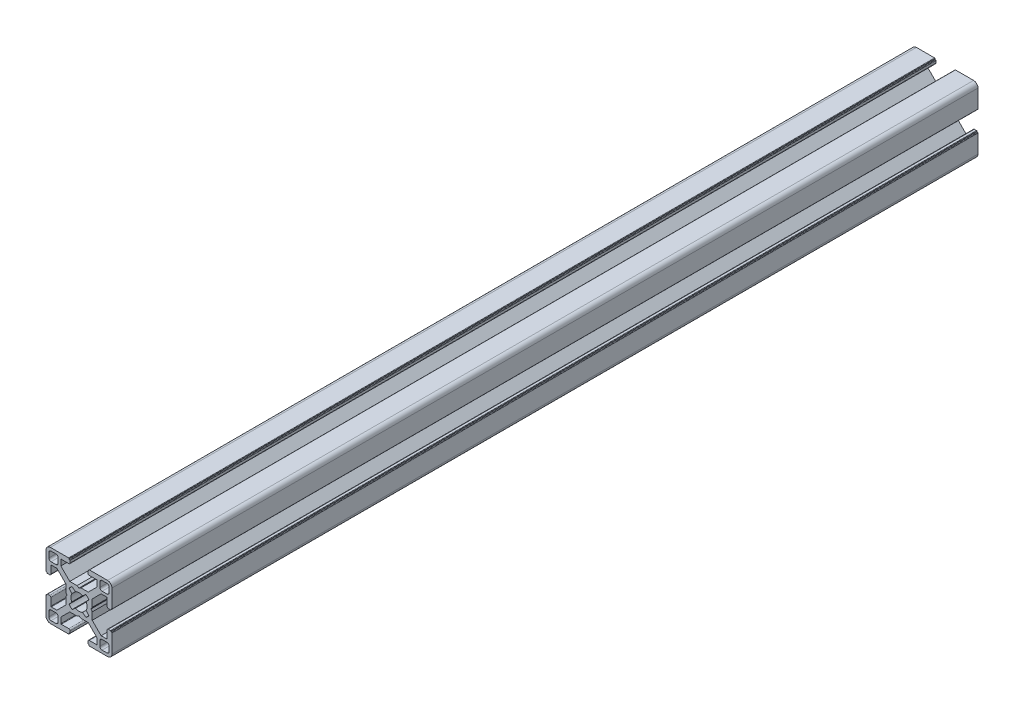
SolidWorks part; units mm, degrees
material "6061 Alloy"
ref_plane "Front" through (0, 0, 0) normal (0, 0, 1) x (1, 0, 0)
ref_plane "Top" through (0, 0, 0) normal (0, 1, 0) x (1, 0, 0)
ref_plane "Right" through (0, 0, 0) normal (1, 0, 0) x (0, 0, -1)
sketch "Sketch1" plane through (0, 0, 0) normal (0, 0, 1) x (1, 0, 0)
  line L0 (13.7, 12.7) -> (13.7, 10.5)
  line L1 (10.5, 9.5) -> (12.7, 9.5)
  line L2 (9.5, 12.7) -> (9.5, 10.5)
  line L3 (10.5, 13.7) -> (12.7, 13.7)
  line L4 (3.1359, 4.5184) -> (1.6001, 3.2806)
  line L5 (3.2806, 1.6001) -> (4.5053, 3.1547)
  line L6 (6.0045, 0.9) -> (5.4849, 0)
  line L7 (6.0045, 4.2045) -> (6.0045, 0.9)
  line L8 (0, -5.4849) -> (0.9, -6)
  line L9 (0.9, -6) -> (4.2045, -6)
  line L10 (4.2045, -6) -> (8.25, -10.05)
  line L11 (8.25, -10.05) -> (8.25, -12.6)
  line L12 (4.65, -12.8) -> (8.05, -12.8)
  line L13 (4.05, -14.3) -> (4.05, -13.4)
  line L14 (4.25, -14.5) -> (4.35, -14.5)
  line L15 (4.55, -14.8) -> (4.55, -14.7)
  line L16 (4.75, -15) -> (13, -15)
  line L17 (15, -13) -> (15, -4.75)
  line L18 (14.7, -4.55) -> (14.8, -4.55)
  line L19 (14.5, -4.35) -> (14.5, -4.25)
  line L20 (13.4, -4.05) -> (14.3, -4.05)
  line L21 (12.8, -8.05) -> (12.8, -4.65)
  line L22 (12.6, -8.25) -> (10.05, -8.25)
  line L23 (10.05, -8.25) -> (6.0045, -4.2045)
  line L24 (6.0045, -4.2045) -> (6.0045, -0.9)
  line L25 (6.0045, -0.9) -> (5.4849, 0)
  line L26 (10.05, 8.25) -> (6.0045, 4.2045)
  line L27 (12.6, 8.25) -> (10.05, 8.25)
  line L28 (12.8, 8.05) -> (12.8, 4.65)
  line L29 (13.4, 4.05) -> (14.3, 4.05)
  line L30 (14.5, 4.35) -> (14.5, 4.25)
  line L31 (14.7, 4.55) -> (14.8, 4.55)
  line L32 (15, 13) -> (15, 4.75)
  line L33 (4.75, 15) -> (13, 15)
  line L34 (4.55, 14.8) -> (4.55, 14.7)
  line L35 (4.25, 14.5) -> (4.35, 14.5)
  line L36 (4.05, 14.3) -> (4.05, 13.4)
  line L37 (4.65, 12.8) -> (8.05, 12.8)
  line L38 (8.25, 10.05) -> (8.25, 12.6)
  line L39 (4.2045, 6) -> (8.25, 10.05)
  line L40 (0.9, 6) -> (4.2045, 6)
  line L41 (0, 5.4849) -> (0.9, 6)
  line L42 (-13.7, -12.7) -> (-13.7, -10.5)
  line L43 (-10.5, -9.5) -> (-12.7, -9.5)
  line L44 (-9.5, -12.7) -> (-9.5, -10.5)
  line L45 (-10.5, -13.7) -> (-12.7, -13.7)
  line L46 (-3.1359, -4.5184) -> (-1.6001, -3.2806)
  line L47 (-3.2806, -1.6001) -> (-4.5053, -3.1547)
  line L48 (0, 5.4849) -> (-0.9, 6)
  line L49 (-0.9, 6) -> (-4.2045, 6)
  line L50 (-4.2045, 6) -> (-8.25, 10.05)
  line L51 (-8.25, 10.05) -> (-8.25, 12.6)
  line L52 (-4.65, 12.8) -> (-8.05, 12.8)
  line L53 (-4.05, 14.3) -> (-4.05, 13.4)
  line L54 (-4.25, 14.5) -> (-4.35, 14.5)
  line L55 (-4.55, 14.8) -> (-4.55, 14.7)
  line L56 (-4.75, 15) -> (-13, 15)
  line L57 (-15, 13) -> (-15, 4.75)
  line L58 (-14.7, 4.55) -> (-14.8, 4.55)
  line L59 (-14.5, 4.35) -> (-14.5, 4.25)
  line L60 (-13.4, 4.05) -> (-14.3, 4.05)
  line L61 (-12.8, 8.05) -> (-12.8, 4.65)
  line L62 (-12.6, 8.25) -> (-10.05, 8.25)
  line L63 (-10.05, 8.25) -> (-6.0045, 4.2045)
  line L64 (-6.0045, -0.9) -> (-5.4849, 0)
  line L65 (-6.0045, -4.2045) -> (-6.0045, -0.9)
  line L66 (-10.05, -8.25) -> (-6.0045, -4.2045)
  line L67 (-12.6, -8.25) -> (-10.05, -8.25)
  line L68 (-12.8, -8.05) -> (-12.8, -4.65)
  line L69 (-13.4, -4.05) -> (-14.3, -4.05)
  line L70 (-14.5, -4.35) -> (-14.5, -4.25)
  line L71 (-14.7, -4.55) -> (-14.8, -4.55)
  line L72 (-15, -13) -> (-15, -4.75)
  line L73 (-4.75, -15) -> (-13, -15)
  line L74 (-4.55, -14.8) -> (-4.55, -14.7)
  line L75 (-4.25, -14.5) -> (-4.35, -14.5)
  line L76 (-4.05, -14.3) -> (-4.05, -13.4)
  line L77 (3.2806, -1.6001) -> (4.5053, -3.1547)
  line L78 (3.1359, -4.5184) -> (1.6001, -3.2806)
  line L79 (-4.65, -12.8) -> (-8.05, -12.8)
  line L80 (-8.25, -10.05) -> (-8.25, -12.6)
  line L81 (-4.2045, -6) -> (-8.25, -10.05)
  line L82 (-0.9, -6) -> (-4.2045, -6)
  line L83 (0, -5.4849) -> (-0.9, -6)
  line L84 (10.5, -13.7) -> (12.7, -13.7)
  line L85 (9.5, -12.7) -> (9.5, -10.5)
  line L86 (10.5, -9.5) -> (12.7, -9.5)
  line L87 (13.7, -12.7) -> (13.7, -10.5)
  line L88 (-6.0045, 4.2045) -> (-6.0045, 0.9)
  line L89 (-6.0045, 0.9) -> (-5.4849, 0)
  line L90 (-3.2806, 1.6001) -> (-4.5053, 3.1547)
  line L91 (-3.1359, 4.5184) -> (-1.6001, 3.2806)
  line L92 (-10.5, 13.7) -> (-12.7, 13.7)
  line L93 (-9.5, 12.7) -> (-9.5, 10.5)
  line L94 (-10.5, 9.5) -> (-12.7, 9.5)
  line L95 (-13.7, 12.7) -> (-13.7, 10.5)
  line L96 (-23.4857, 0) -> (20.9308, 0) construction
  line L97 (0, 17.9563) -> (0, -17.361) construction
  arc A0 (13.7, 12.7) -> (12.7, 13.7) centre (12.7, 12.7) ccw
  arc A1 (12.7, 9.5) -> (13.7, 10.5) centre (12.7, 10.5) ccw
  arc A2 (9.5, 10.5) -> (10.5, 9.5) centre (10.5, 10.5) ccw
  arc A3 (10.5, 13.7) -> (9.5, 12.7) centre (10.5, 12.7) ccw
  arc A4 (1.6001, 3.2806) -> (-1.6001, 3.2806) centre (0, 0) ccw
  arc A5 (8.25, -12.6) -> (8.05, -12.8) centre (8.05, -12.6) cw
  arc A6 (4.65, -12.8) -> (4.05, -13.4) centre (4.65, -13.4) ccw
  arc A7 (4.05, -14.3) -> (4.25, -14.5) centre (4.25, -14.3) ccw
  arc A8 (4.35, -14.5) -> (4.55, -14.7) centre (4.35, -14.7) cw
  arc A9 (4.55, -14.8) -> (4.75, -15) centre (4.75, -14.8) ccw
  arc A10 (13, -15) -> (15, -13) centre (13, -13) ccw
  arc A11 (15, -4.75) -> (14.8, -4.55) centre (14.8, -4.75) ccw
  arc A12 (14.7, -4.55) -> (14.5, -4.35) centre (14.7, -4.35) cw
  arc A13 (14.5, -4.25) -> (14.3, -4.05) centre (14.3, -4.25) ccw
  arc A14 (13.4, -4.05) -> (12.8, -4.65) centre (13.4, -4.65) ccw
  arc A15 (12.8, -8.05) -> (12.6, -8.25) centre (12.6, -8.05) cw
  arc A16 (4.5053, 3.1547) -> (3.1359, 4.5184) centre (0, 0) ccw
  arc A17 (12.8, 8.05) -> (12.6, 8.25) centre (12.6, 8.05) ccw
  arc A18 (13.4, 4.05) -> (12.8, 4.65) centre (13.4, 4.65) cw
  arc A19 (14.5, 4.25) -> (14.3, 4.05) centre (14.3, 4.25) cw
  arc A20 (14.7, 4.55) -> (14.5, 4.35) centre (14.7, 4.35) ccw
  arc A21 (15, 4.75) -> (14.8, 4.55) centre (14.8, 4.75) cw
  arc A22 (13, 15) -> (15, 13) centre (13, 13) cw
  arc A23 (4.55, 14.8) -> (4.75, 15) centre (4.75, 14.8) cw
  arc A24 (4.35, 14.5) -> (4.55, 14.7) centre (4.35, 14.7) ccw
  arc A25 (4.05, 14.3) -> (4.25, 14.5) centre (4.25, 14.3) cw
  arc A26 (4.65, 12.8) -> (4.05, 13.4) centre (4.65, 13.4) cw
  arc A27 (8.25, 12.6) -> (8.05, 12.8) centre (8.05, 12.6) ccw
  arc A28 (-13.7, -12.7) -> (-12.7, -13.7) centre (-12.7, -12.7) ccw
  arc A29 (-12.7, -9.5) -> (-13.7, -10.5) centre (-12.7, -10.5) ccw
  arc A30 (-9.5, -10.5) -> (-10.5, -9.5) centre (-10.5, -10.5) ccw
  arc A31 (-10.5, -13.7) -> (-9.5, -12.7) centre (-10.5, -12.7) ccw
  arc A32 (-4.5053, -3.1547) -> (-3.1359, -4.5184) centre (0, 0) ccw
  arc A33 (-3.2806, 1.6001) -> (-3.2806, -1.6001) centre (0, 0) ccw
  arc A34 (-8.25, 12.6) -> (-8.05, 12.8) centre (-8.05, 12.6) cw
  arc A35 (-4.65, 12.8) -> (-4.05, 13.4) centre (-4.65, 13.4) ccw
  arc A36 (-4.05, 14.3) -> (-4.25, 14.5) centre (-4.25, 14.3) ccw
  arc A37 (-4.35, 14.5) -> (-4.55, 14.7) centre (-4.35, 14.7) cw
  arc A38 (-4.55, 14.8) -> (-4.75, 15) centre (-4.75, 14.8) ccw
  arc A39 (-13, 15) -> (-15, 13) centre (-13, 13) ccw
  arc A40 (-15, 4.75) -> (-14.8, 4.55) centre (-14.8, 4.75) ccw
  arc A41 (-14.7, 4.55) -> (-14.5, 4.35) centre (-14.7, 4.35) cw
  arc A42 (-14.5, 4.25) -> (-14.3, 4.05) centre (-14.3, 4.25) ccw
  arc A43 (-13.4, 4.05) -> (-12.8, 4.65) centre (-13.4, 4.65) ccw
  arc A44 (-12.8, 8.05) -> (-12.6, 8.25) centre (-12.6, 8.05) cw
  arc A45 (-4.5053, 3.1547) -> (-3.1359, 4.5184) centre (0, 0) cw
  arc A46 (-12.8, -8.05) -> (-12.6, -8.25) centre (-12.6, -8.05) ccw
  arc A47 (-13.4, -4.05) -> (-12.8, -4.65) centre (-13.4, -4.65) cw
  arc A48 (-14.5, -4.25) -> (-14.3, -4.05) centre (-14.3, -4.25) cw
  arc A49 (3.2806, 1.6001) -> (3.2806, -1.6001) centre (0, 0) cw
  arc A50 (4.5053, -3.1547) -> (3.1359, -4.5184) centre (0, 0) cw
  arc A51 (1.6001, -3.2806) -> (-1.6001, -3.2806) centre (0, 0) cw
  arc A52 (-14.7, -4.55) -> (-14.5, -4.35) centre (-14.7, -4.35) ccw
  arc A53 (-15, -4.75) -> (-14.8, -4.55) centre (-14.8, -4.75) cw
  arc A54 (-13, -15) -> (-15, -13) centre (-13, -13) cw
  arc A55 (-4.55, -14.8) -> (-4.75, -15) centre (-4.75, -14.8) cw
  arc A56 (10.5, -13.7) -> (9.5, -12.7) centre (10.5, -12.7) cw
  arc A57 (9.5, -10.5) -> (10.5, -9.5) centre (10.5, -10.5) cw
  arc A58 (12.7, -9.5) -> (13.7, -10.5) centre (12.7, -10.5) cw
  arc A59 (13.7, -12.7) -> (12.7, -13.7) centre (12.7, -12.7) cw
  arc A60 (-4.35, -14.5) -> (-4.55, -14.7) centre (-4.35, -14.7) ccw
  arc A61 (-4.05, -14.3) -> (-4.25, -14.5) centre (-4.25, -14.3) cw
  arc A62 (-4.65, -12.8) -> (-4.05, -13.4) centre (-4.65, -13.4) cw
  arc A63 (-8.25, -12.6) -> (-8.05, -12.8) centre (-8.05, -12.6) ccw
  arc A64 (-10.5, 13.7) -> (-9.5, 12.7) centre (-10.5, 12.7) cw
  arc A65 (-9.5, 10.5) -> (-10.5, 9.5) centre (-10.5, 10.5) cw
  arc A66 (-12.7, 9.5) -> (-13.7, 10.5) centre (-12.7, 10.5) cw
  arc A67 (-13.7, 12.7) -> (-12.7, 13.7) centre (-12.7, 12.7) cw
  point P81 (15, 15)
  point P82 (0, 15)
  point P203 (0, -15)
  point P204 (15, -15)
  point P206 (0, 0)
  point P207 (15, 0)
  point P219 (-15, 0)
  point P220 (-15, -15)
  point P221 (-15, 15)
  dimension "D6" = 7.3
  dimension "D7" = 11
  dimension "D1" = 30
  dimension "D2" = 15
  dimension "D3" = 30
  dimension "D4" = 8.1
  dimension "D5" = 9
  dimension "D8" = 8.1
extrude "Boss-Extrude1" add sketch "Sketch1" along normal blind 393.7
